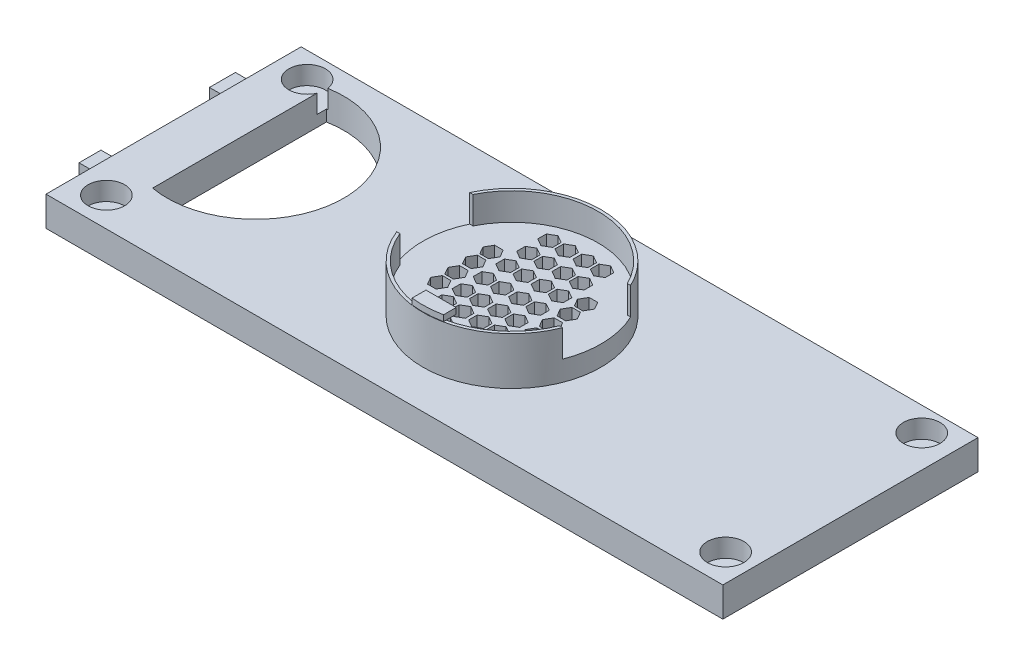
SolidWorks part; units mm, degrees
ref_plane "Front Plane" through (0, 0, 0) normal (0, 0, 1) x (1, 0, 0)
ref_plane "Top Plane" through (0, 0, 0) normal (0, 1, 0) x (1, 0, 0)
ref_plane "Right Plane" through (0, 0, 0) normal (1, 0, 0) x (0, 0, -1)
sketch "Sketch1" plane through (0, 0, 0) normal (0, 1, 0) x (1, 0, 0)
  line L1 (57, -21.4874) -> (-57, -21.4874)
  line L2 (57, -21.4874) -> (57, 21.4874)
  line L3 (57, 21.4874) -> (-57, 21.4874)
  line L4 (-57, -21.4874) -> (-57, 21.4874)
  line L5 (57, -21.4874) -> (-57, 21.4874) construction
  line L6 (57, 21.4874) -> (-57, -21.4874) construction
  point P0 (0, 0)
extrude "Boss-Extrude1" add sketch "Sketch1" along normal blind 5
sketch "Sketch2" plane through (0, 5, 0) normal (0, 1, 0) x (1, 0, 0)
  line L0 (-57, 21.4874) -> (-53.5, 21.4874) construction
  line L1 (57, 21.4874) -> (-57, 21.4874) construction
sketch "Sketch3" plane through (0, 5, 0) normal (0, 1, 0) x (1, 0, 0)
  line L0 (-51.7531, 23.5004) -> (-51.7531, -21.2397) construction
  line L1 (57.5677, 22.3499) -> (57.5677, -22.3902) construction
  line L2 (-55.25, 21.4874) -> (-55.25, -21.4874) construction
  line L3 (-57, 21.4874) -> (-53.5, 21.4874) construction
  line L4 (-57, -21.4874) -> (57, -21.4874) construction
  line L9 (-57, 0) -> (57, 0) construction
  line L10 (-57, 21.4874) -> (-57, -21.4874) construction
  line L11 (57, -21.4874) -> (57, 21.4874) construction
  line L12 (-51.7531, 17.2469) -> (51.585, 17.4252) construction
  line L13 (-0.0841, 17.3361) -> (-0.0841, -21.4874) construction
  line L14 (0, 0) -> (0, -21.4874) construction
  line L15 (-51.7531, -16.5649) -> (55.5178, -16.4581) construction
  line L16 (51.585, 17.4252) -> (52.4378, -16.4581) construction
  circle A0 centre (-51.7531, 17.2469) radius 3.08
  circle A1 centre (-51.7531, -16.5649) radius 3.08
  circle A2 centre (51.585, 17.4252) radius 3.08
  circle A3 centre (52.4378, -16.4581) radius 3.08
extrude "Cut-Extrude1" cut sketch "Sketch3" against normal blind 3.1
sketch "Sketch5" plane through (-57, 0, 0) normal (-1, 0, 0) x (0, 0, 1)
  line L0 (-22.3979, 2.4922) -> (22.3422, 2.4922) construction
  line L1 (-13.513, 1.7003) -> (-13.513, 3.7003)
  line L2 (-13.513, 1.7003) -> (-9.1383, 1.7003)
  line L3 (-9.1383, 1.7003) -> (-9.1383, 3.7003)
  line L4 (-13.513, 3.7003) -> (-9.1383, 3.7003)
  line L5 (-9.1383, 1.7003) -> (9.1276, 1.7003) construction
  line L9 (12.8259, 3.6937) -> (9.1276, 3.6937)
  line L10 (9.1276, 1.6901) -> (9.1276, 3.6937)
  line L11 (12.8259, 1.6901) -> (9.1276, 1.6901)
  line L12 (12.8259, 1.6901) -> (12.8259, 3.6937)
  line L13 (-21.4874, 2.5) -> (21.4874, 2.5) construction
  line L14 (-21.4874, 5) -> (-21.4874, 0) construction
  line L15 (21.4874, 5) -> (21.4874, 0) construction
  point P2 (-11.2129, 2.4922)
  point P11 (11.1572, 2.4922)
  dimension "D1" = 2
extrude "Boss-Extrude2" add sketch "Sketch5" along normal blind 3.1
sketch "Sketch6" plane through (0, 5, 0) normal (0, 1, 0) x (1, 0, 0)
  circle A0 centre (0, 0) radius 15
extrude "Boss-Extrude3" add sketch "Sketch6" along normal blind 8
sketch "Sketch8" plane through (0, 13, 0) normal (0, 1, 0) x (1, 0, 0)
  circle A0 centre (0, 0) radius 14.5
extrude "Cut-Extrude2" cut sketch "Sketch8" against normal blind 4.6
sketch "Sketch9" plane through (0, 8.4, 0) normal (0, 1, 0) x (1, 0, 0)
  line L0 (-18.3405, -5.4356) -> (20.9474, -5.4356)
  line L1 (20.9474, -5.4356) -> (20.9474, 6.4298)
  line L2 (20.9474, 6.4298) -> (-18.3405, 6.4298)
  line L3 (-18.3405, 6.4298) -> (-18.3405, -5.4356)
extrude "Cut-Extrude5" cut sketch "Sketch9" along normal blind 9.6
ref_plane "Plane1" through (13.9805, 13, 5.4356) normal (0.3624, 0, -0.932) x (-0.932, 0, -0.3624)
sketch "Sketch11" plane through (0, 13, 0) normal (0, 1, 0) x (1, 0, 0)
  line L0 (-2.0086, -12.4834) -> (-2.0086, -14.8138)
  line L1 (0, -12.4834) -> (-2.0086, -12.4834)
  line L3 (-2.0086, -12.4834) -> (3.0728, -12.4834)
  line L5 (3.0728, -12.4834) -> (3.0728, -14.6075)
  arc A3 (-2.0086, -14.8138) -> (3.0728, -14.6075) centre (-0.1027, 0.9217) ccw
extrude "Boss-Extrude5" add sketch "Sketch11" along normal blind 1 contours L3 L5 A3 L0
sketch "Sketch12" plane through (0, 0, 0) normal (0, -1, 0) x (1, 0, 0)
  line L0 (0, 14.5) -> (0, -14.5) construction
  line L1 (-15, 0) -> (15, 0) construction
  line L17 (-1.3814, -4.9711) -> (-0.1328, -4.2503)
  line L36 (-0.1328, -4.2503) -> (-0.1328, -2.8085)
  line L37 (-0.1328, -2.8085) -> (-1.3814, -2.0876)
  line L38 (-1.3814, -2.0876) -> (-2.63, -2.8085)
  line L39 (-2.63, -2.8085) -> (-2.63, -4.2503)
  line L40 (-2.63, -4.2503) -> (-1.3814, -4.9711)
  line L46 (-4.2896, -4.9711) -> (-3.041, -4.2503)
  line L47 (-3.041, -4.2503) -> (-3.041, -2.8085)
  line L48 (-3.041, -2.8085) -> (-4.2896, -2.0876)
  line L49 (-4.2896, -2.0876) -> (-5.5382, -2.8085)
  line L50 (-5.5382, -2.8085) -> (-5.5382, -4.2503)
  line L51 (-5.5382, -4.2503) -> (-4.2896, -4.9711)
  line L52 (4.5464, -5.001) -> (5.795, -4.2801)
  line L53 (5.795, -4.2801) -> (5.795, -2.8384)
  line L54 (5.795, -2.8384) -> (4.5464, -2.1175)
  line L55 (4.5464, -2.1175) -> (3.2978, -2.8384)
  line L56 (3.2978, -2.8384) -> (3.2978, -4.2801)
  line L57 (3.2978, -4.2801) -> (4.5464, -5.001)
  line L58 (1.6382, -5.001) -> (2.8868, -4.2801)
  line L59 (2.8868, -4.2801) -> (2.8868, -2.8384)
  line L60 (2.8868, -2.8384) -> (1.6382, -2.1175)
  line L61 (1.6382, -2.1175) -> (0.3896, -2.8384)
  line L62 (0.3896, -2.8384) -> (0.3896, -4.2801)
  line L63 (0.3896, -4.2801) -> (1.6382, -5.001)
  line L64 (-1.4428, -1.2342) -> (-0.1942, -0.5133)
  line L65 (-0.1942, -0.5133) -> (-0.1942, 0.9284)
  line L66 (-0.1942, 0.9284) -> (-1.4428, 1.6493)
  line L67 (-1.4428, 1.6493) -> (-2.6914, 0.9284)
  line L68 (-2.6914, 0.9284) -> (-2.6914, -0.5133)
  line L69 (-2.6914, -0.5133) -> (-1.4428, -1.2342)
  line L70 (-4.351, -1.2342) -> (-3.1025, -0.5133)
  line L71 (-3.1025, -0.5133) -> (-3.1025, 0.9284)
  line L72 (-3.1025, 0.9284) -> (-4.351, 1.6493)
  line L73 (-4.351, 1.6493) -> (-5.5996, 0.9284)
  line L74 (-5.5996, 0.9284) -> (-5.5996, -0.5133)
  line L75 (-5.5996, -0.5133) -> (-4.351, -1.2342)
  line L76 (4.4849, -1.2641) -> (5.7335, -0.5432)
  line L77 (5.7335, -0.5432) -> (5.7335, 0.8985)
  line L78 (5.7335, 0.8985) -> (4.4849, 1.6194)
  line L79 (4.4849, 1.6194) -> (3.2363, 0.8985)
  line L80 (3.2363, 0.8985) -> (3.2363, -0.5432)
  line L81 (3.2363, -0.5432) -> (4.4849, -1.2641)
  line L82 (1.5767, -1.2641) -> (2.8253, -0.5432)
  line L83 (2.8253, -0.5432) -> (2.8253, 0.8985)
  line L84 (2.8253, 0.8985) -> (1.5767, 1.6194)
  line L85 (1.5767, 1.6194) -> (0.3281, 0.8985)
  line L86 (0.3281, 0.8985) -> (0.3281, -0.5432)
  line L87 (0.3281, -0.5432) -> (1.5767, -1.2641)
  line L88 (-1.4428, 2.3085) -> (-0.1942, 3.0293)
  line L89 (-0.1942, 3.0293) -> (-0.1942, 4.4711)
  line L90 (-0.1942, 4.4711) -> (-1.4428, 5.192)
  line L91 (-1.4428, 5.192) -> (-2.6914, 4.4711)
  line L92 (-2.6914, 4.4711) -> (-2.6914, 3.0293)
  line L93 (-2.6914, 3.0293) -> (-1.4428, 2.3085)
  line L94 (-4.351, 2.3085) -> (-3.1025, 3.0293)
  line L95 (-3.1025, 3.0293) -> (-3.1025, 4.4711)
  line L96 (-3.1025, 4.4711) -> (-4.351, 5.192)
  line L97 (-4.351, 5.192) -> (-5.5996, 4.4711)
  line L98 (-5.5996, 4.4711) -> (-5.5996, 3.0293)
  line L99 (-5.5996, 3.0293) -> (-4.351, 2.3085)
  line L100 (4.4849, 2.2786) -> (5.7335, 2.9995)
  line L101 (5.7335, 2.9995) -> (5.7335, 4.4412)
  line L102 (5.7335, 4.4412) -> (4.4849, 5.1621)
  line L103 (4.4849, 5.1621) -> (3.2363, 4.4412)
  line L104 (3.2363, 4.4412) -> (3.2363, 2.9995)
  line L105 (3.2363, 2.9995) -> (4.4849, 2.2786)
  line L106 (1.5767, 2.2786) -> (2.8253, 2.9995)
  line L107 (2.8253, 2.9995) -> (2.8253, 4.4412)
  line L108 (2.8253, 4.4412) -> (1.5767, 5.1621)
  line L109 (1.5767, 5.1621) -> (0.3281, 4.4412)
  line L110 (0.3281, 4.4412) -> (0.3281, 2.9995)
  line L111 (0.3281, 2.9995) -> (1.5767, 2.2786)
  line L112 (-1.4248, 5.5165) -> (-0.1763, 6.2374)
  line L113 (-0.1763, 6.2374) -> (-0.1763, 7.6792)
  line L114 (-0.1763, 7.6792) -> (-1.4248, 8.4)
  line L115 (-1.4248, 8.4) -> (-2.6734, 7.6792)
  line L116 (-2.6734, 7.6792) -> (-2.6734, 6.2374)
  line L117 (-2.6734, 6.2374) -> (-1.4248, 5.5165)
  line L118 (-4.3331, 5.5165) -> (-3.0845, 6.2374)
  line L119 (-3.0845, 6.2374) -> (-3.0845, 7.6792)
  line L120 (-3.0845, 7.6792) -> (-4.3331, 8.4)
  line L121 (-4.3331, 8.4) -> (-5.5816, 7.6792)
  line L122 (-5.5816, 7.6792) -> (-5.5816, 6.2374)
  line L123 (-5.5816, 6.2374) -> (-4.3331, 5.5165)
  line L124 (4.5029, 5.4867) -> (5.7515, 6.2075)
  line L125 (5.7515, 6.2075) -> (5.7515, 7.6493)
  line L126 (5.7515, 7.6493) -> (4.5029, 8.3702)
  line L127 (4.5029, 8.3702) -> (3.2543, 7.6493)
  line L128 (3.2543, 7.6493) -> (3.2543, 6.2075)
  line L129 (3.2543, 6.2075) -> (4.5029, 5.4867)
  line L130 (1.5947, 5.4867) -> (2.8433, 6.2075)
  line L131 (2.8433, 6.2075) -> (2.8433, 7.6493)
  line L132 (2.8433, 7.6493) -> (1.5947, 8.3702)
  line L133 (1.5947, 8.3702) -> (0.3461, 7.6493)
  line L134 (0.3461, 7.6493) -> (0.3461, 6.2075)
  line L135 (0.3461, 6.2075) -> (1.5947, 5.4867)
  line L136 (-1.4064, 8.9229) -> (-0.1579, 9.6438)
  line L137 (-0.1579, 9.6438) -> (-0.1579, 11.0856)
  line L138 (-0.1579, 11.0856) -> (-1.4064, 11.8064)
  line L139 (-1.4064, 11.8064) -> (-2.655, 11.0856)
  line L140 (-2.655, 11.0856) -> (-2.655, 9.6438)
  line L141 (-2.655, 9.6438) -> (-1.4064, 8.9229)
  line L142 (-4.3147, 8.9229) -> (-3.0661, 9.6438)
  line L143 (-3.0661, 9.6438) -> (-3.0661, 11.0856)
  line L144 (-3.0661, 11.0856) -> (-4.3147, 11.8064)
  line L145 (-4.3147, 11.8064) -> (-5.5633, 11.0856)
  line L146 (-5.5633, 11.0856) -> (-5.5633, 9.6438)
  line L147 (-5.5633, 9.6438) -> (-4.3147, 8.9229)
  line L148 (4.5213, 8.8931) -> (5.7699, 9.6139)
  line L149 (5.7699, 9.6139) -> (5.7699, 11.0557)
  line L150 (5.7699, 11.0557) -> (4.5213, 11.7766)
  line L151 (4.5213, 11.7766) -> (3.2727, 11.0557)
  line L152 (3.2727, 11.0557) -> (3.2727, 9.6139)
  line L153 (3.2727, 9.6139) -> (4.5213, 8.8931)
  line L154 (1.6131, 8.8931) -> (2.8617, 9.6139)
  line L155 (2.8617, 9.6139) -> (2.8617, 11.0557)
  line L156 (2.8617, 11.0557) -> (1.6131, 11.7766)
  line L157 (1.6131, 11.7766) -> (0.3645, 11.0557)
  line L158 (0.3645, 11.0557) -> (0.3645, 9.6139)
  line L159 (0.3645, 9.6139) -> (1.6131, 8.8931)
  line L160 (-1.4667, -8.5789) -> (-0.2181, -7.858)
  line L161 (-0.2181, -7.858) -> (-0.2181, -6.4163)
  line L162 (-0.2181, -6.4163) -> (-1.4667, -5.6954)
  line L163 (-1.4667, -5.6954) -> (-2.7153, -6.4163)
  line L164 (-2.7153, -6.4163) -> (-2.7153, -7.858)
  line L165 (-2.7153, -7.858) -> (-1.4667, -8.5789)
  line L166 (-4.3749, -8.5789) -> (-3.1263, -7.858)
  line L167 (-3.1263, -7.858) -> (-3.1263, -6.4163)
  line L168 (-3.1263, -6.4163) -> (-4.3749, -5.6954)
  line L169 (-4.3749, -5.6954) -> (-5.6235, -6.4163)
  line L170 (-5.6235, -6.4163) -> (-5.6235, -7.858)
  line L171 (-5.6235, -7.858) -> (-4.3749, -8.5789)
  line L172 (4.461, -8.6088) -> (5.7096, -7.8879)
  line L173 (5.7096, -7.8879) -> (5.7096, -6.4461)
  line L174 (5.7096, -6.4461) -> (4.461, -5.7253)
  line L175 (4.461, -5.7253) -> (3.2124, -6.4461)
  line L176 (3.2124, -6.4461) -> (3.2124, -7.8879)
  line L177 (3.2124, -7.8879) -> (4.461, -8.6088)
  line L178 (1.5528, -8.6088) -> (2.8014, -7.8879)
  line L179 (2.8014, -7.8879) -> (2.8014, -6.4461)
  line L180 (2.8014, -6.4461) -> (1.5528, -5.7253)
  line L181 (1.5528, -5.7253) -> (0.3042, -6.4461)
  line L182 (0.3042, -6.4461) -> (0.3042, -7.8879)
  line L183 (0.3042, -7.8879) -> (1.5528, -8.6088)
  line L184 (-1.5025, -12.1629) -> (-0.2539, -11.442)
  line L185 (-0.2539, -11.442) -> (-0.2539, -10.0003)
  line L186 (-0.2539, -10.0003) -> (-1.5025, -9.2794)
  line L187 (-1.5025, -9.2794) -> (-2.7511, -10.0003)
  line L188 (-2.7511, -10.0003) -> (-2.7511, -11.442)
  line L189 (-2.7511, -11.442) -> (-1.5025, -12.1629)
  line L190 (-4.4107, -12.1629) -> (-3.1621, -11.442)
  line L191 (-3.1621, -11.442) -> (-3.1621, -10.0003)
  line L192 (-3.1621, -10.0003) -> (-4.4107, -9.2794)
  line L193 (-4.4107, -9.2794) -> (-5.6593, -10.0003)
  line L194 (-5.6593, -10.0003) -> (-5.6593, -11.442)
  line L195 (-5.6593, -11.442) -> (-4.4107, -12.1629)
  line L196 (4.4253, -12.1928) -> (5.6739, -11.4719)
  line L197 (5.6739, -11.4719) -> (5.6739, -10.0301)
  line L198 (5.6739, -10.0301) -> (4.4253, -9.3093)
  line L199 (4.4253, -9.3093) -> (3.1767, -10.0301)
  line L200 (3.1767, -10.0301) -> (3.1767, -11.4719)
  line L201 (3.1767, -11.4719) -> (4.4253, -12.1928)
  line L202 (1.5171, -12.1928) -> (2.7657, -11.4719)
  line L203 (2.7657, -11.4719) -> (2.7657, -10.0301)
  line L204 (2.7657, -10.0301) -> (1.5171, -9.3093)
  line L205 (1.5171, -9.3093) -> (0.2685, -10.0301)
  line L206 (0.2685, -10.0301) -> (0.2685, -11.4719)
  line L207 (0.2685, -11.4719) -> (1.5171, -12.1928)
  line L208 (-6.2102, -1.2905) -> (-6.9311, -0.0419)
  line L209 (-6.9311, -0.0419) -> (-8.3728, -0.0419)
  line L210 (-8.3728, -0.0419) -> (-9.0937, -1.2905)
  line L211 (-9.0937, -1.2905) -> (-8.3728, -2.539)
  line L212 (-8.3728, -2.539) -> (-6.9311, -2.539)
  line L213 (-6.9311, -2.539) -> (-6.2102, -1.2905)
  line L214 (-6.2102, -4.1987) -> (-6.9311, -2.9501)
  line L215 (-6.9311, -2.9501) -> (-8.3728, -2.9501)
  line L216 (-8.3728, -2.9501) -> (-9.0937, -4.1987)
  line L217 (-9.0937, -4.1987) -> (-8.3728, -5.4473)
  line L218 (-8.3728, -5.4473) -> (-6.9311, -5.4473)
  line L219 (-6.9311, -5.4473) -> (-6.2102, -4.1987)
  line L220 (-6.1803, 4.6373) -> (-6.9012, 5.8859)
  line L221 (-6.9012, 5.8859) -> (-8.3429, 5.8859)
  line L222 (-8.3429, 5.8859) -> (-9.0638, 4.6373)
  line L223 (-9.0638, 4.6373) -> (-8.3429, 3.3887)
  line L224 (-8.3429, 3.3887) -> (-6.9012, 3.3887)
  line L225 (-6.9012, 3.3887) -> (-6.1803, 4.6373)
  line L226 (-6.1803, 1.7291) -> (-6.9012, 2.9777)
  line L227 (-6.9012, 2.9777) -> (-8.3429, 2.9777)
  line L228 (-8.3429, 2.9777) -> (-9.0638, 1.7291)
  line L229 (-9.0638, 1.7291) -> (-8.3429, 0.4805)
  line L230 (-8.3429, 0.4805) -> (-6.9012, 0.4805)
  line L231 (-6.9012, 0.4805) -> (-6.1803, 1.7291)
  line L232 (9.3641, -1.6319) -> (8.6432, -0.3833)
  line L233 (8.6432, -0.3833) -> (7.2014, -0.3833)
  line L234 (7.2014, -0.3833) -> (6.4806, -1.6319)
  line L235 (6.4806, -1.6319) -> (7.2014, -2.8804)
  line L236 (7.2014, -2.8804) -> (8.6432, -2.8804)
  line L237 (8.6432, -2.8804) -> (9.3641, -1.6319)
  line L238 (9.3641, -4.5401) -> (8.6432, -3.2915)
  line L239 (8.6432, -3.2915) -> (7.2014, -3.2915)
  line L240 (7.2014, -3.2915) -> (6.4806, -4.5401)
  line L241 (6.4806, -4.5401) -> (7.2014, -5.7887)
  line L242 (7.2014, -5.7887) -> (8.6432, -5.7887)
  line L243 (8.6432, -5.7887) -> (9.3641, -4.5401)
  line L244 (9.3939, 4.2959) -> (8.6731, 5.5445)
  line L245 (8.6731, 5.5445) -> (7.2313, 5.5445)
  line L246 (7.2313, 5.5445) -> (6.5104, 4.2959)
  line L247 (6.5104, 4.2959) -> (7.2313, 3.0473)
  line L248 (7.2313, 3.0473) -> (8.6731, 3.0473)
  line L249 (8.6731, 3.0473) -> (9.3939, 4.2959)
  line L250 (9.3939, 1.3877) -> (8.6731, 2.6363)
  line L251 (8.6731, 2.6363) -> (7.2313, 2.6363)
  line L252 (7.2313, 2.6363) -> (6.5104, 1.3877)
  line L253 (6.5104, 1.3877) -> (7.2313, 0.1391)
  line L254 (7.2313, 0.1391) -> (8.6731, 0.1391)
  line L255 (8.6731, 0.1391) -> (9.3939, 1.3877)
  circle A0 centre (-1.4248, 6.9583) radius 1.2486 construction
  circle A12 centre (-1.3814, -3.5294) radius 1.2486 construction
  circle A14 centre (-4.2896, -3.5294) radius 1.2486 construction
  circle A15 centre (4.5464, -3.5593) radius 1.2486 construction
  circle A16 centre (1.6382, -3.5593) radius 1.2486 construction
  circle A17 centre (-1.4428, 0.2075) radius 1.2486 construction
  circle A18 centre (-4.351, 0.2075) radius 1.2486 construction
  circle A19 centre (4.4849, 0.1777) radius 1.2486 construction
  circle A20 centre (1.5767, 0.1777) radius 1.2486 construction
  circle A21 centre (-1.4428, 3.7502) radius 1.2486 construction
  circle A22 centre (-4.351, 3.7502) radius 1.2486 construction
  circle A23 centre (4.4849, 3.7203) radius 1.2486 construction
  circle A24 centre (1.5767, 3.7203) radius 1.2486 construction
  circle A25 centre (-4.3331, 6.9583) radius 1.2486 construction
  circle A26 centre (4.5029, 6.9284) radius 1.2486 construction
  circle A27 centre (1.5947, 6.9284) radius 1.2486 construction
  circle A28 centre (-1.4064, 10.3647) radius 1.2486 construction
  circle A29 centre (-4.3147, 10.3647) radius 1.2486 construction
  circle A30 centre (4.5213, 10.3348) radius 1.2486 construction
  circle A31 centre (1.6131, 10.3348) radius 1.2486 construction
  circle A32 centre (-1.4667, -7.1372) radius 1.2486 construction
  circle A33 centre (-4.3749, -7.1372) radius 1.2486 construction
  circle A34 centre (4.461, -7.167) radius 1.2486 construction
  circle A35 centre (1.5528, -7.167) radius 1.2486 construction
  circle A36 centre (-1.5025, -10.7211) radius 1.2486 construction
  circle A37 centre (-4.4107, -10.7211) radius 1.2486 construction
  circle A38 centre (4.4253, -10.751) radius 1.2486 construction
  circle A39 centre (1.5171, -10.751) radius 1.2486 construction
  circle A40 centre (-7.6519, -1.2905) radius 1.2486 construction
  circle A41 centre (-7.6519, -4.1987) radius 1.2486 construction
  circle A42 centre (-7.6221, 4.6373) radius 1.2486 construction
  circle A43 centre (-7.6221, 1.7291) radius 1.2486 construction
  circle A44 centre (7.9223, -1.6319) radius 1.2486 construction
  circle A45 centre (7.9223, -4.5401) radius 1.2486 construction
  circle A46 centre (7.9522, 4.2959) radius 1.2486 construction
  circle A47 centre (7.9522, 1.3877) radius 1.2486 construction
extrude "Cut-Extrude6" cut sketch "Sketch12" against normal blind 10
sketch "Sketch13" plane through (0, 0, 0) normal (0, -1, 0) x (1, 0, 0)
  line L0 (-57, 21.4874) -> (-48.9, 21.4874)
  line L1 (-57, 21.4874) -> (57, 21.4874) construction
  line L2 (-48.9, 21.4874) -> (-48.9, -21.4874) construction
  line L3 (57, -21.4874) -> (-57, -21.4874) construction
  line L4 (-48.9, 11.6273) -> (-48.9, -17.6476)
  arc A0 (-48.9, 11.6273) -> (-48.9, -17.6476) centre (-46.2068, -3.0101) cw
extrude "Cut-Extrude7" cut sketch "Sketch13" against normal blind 10 contours A0 L4
